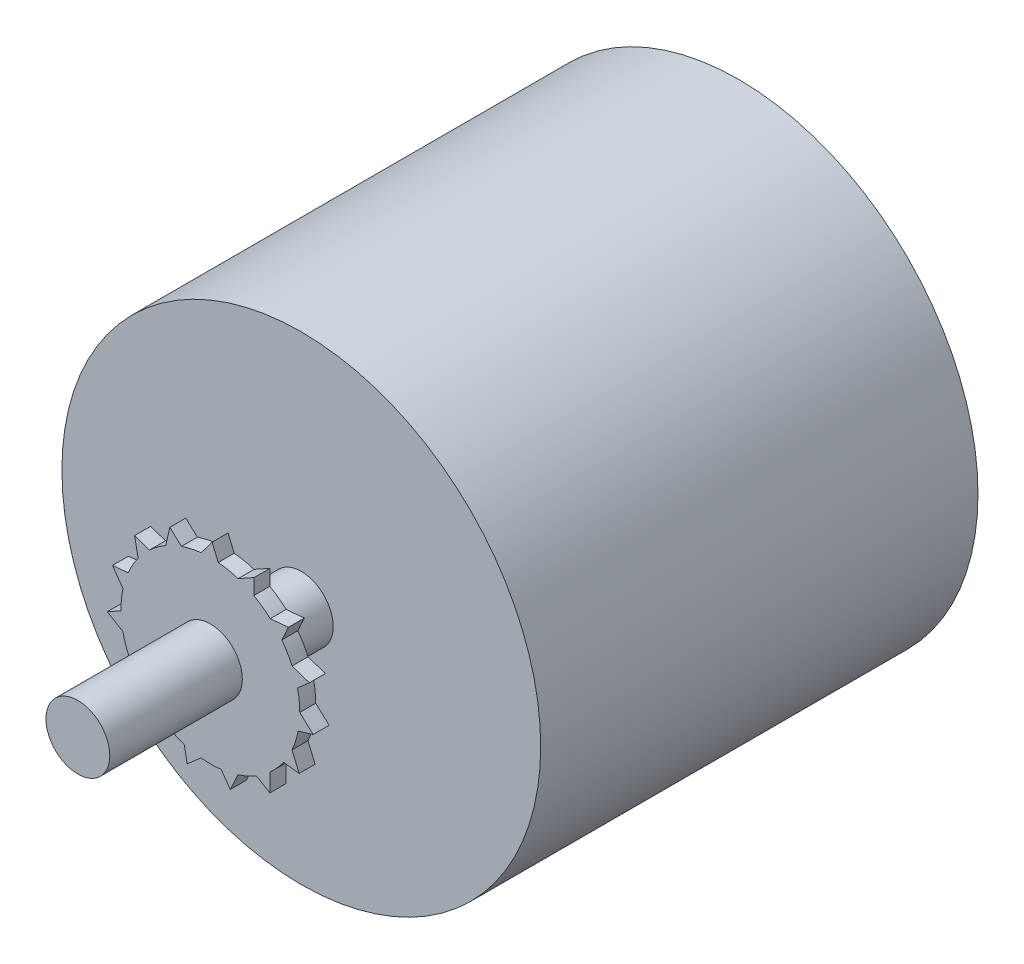
SolidWorks part; units mm, degrees
ref_plane "Front Plane" through (0, 0, 0) normal (0, 0, 1) x (1, 0, 0)
ref_plane "Top Plane" through (0, 0, 0) normal (0, 1, 0) x (1, 0, 0)
ref_plane "Right Plane" through (0, 0, 0) normal (1, 0, 0) x (0, 0, -1)
sketch "Sketch1" plane through (0, 0, 0) normal (0, 0, 1) x (1, 0, 0)
  circle A0 centre (0, 0) radius 75
  dimension "D1" = 150
extrude "Boss-Extrude1" add sketch "Sketch1" along normal blind 137
sketch "Sketch2" plane through (0, 0, 137) normal (0, 0, 1) x (1, 0, 0)
  line L0 (20.6249, 0) -> (-20.6249, 0) construction
  circle A0 centre (0, 0) radius 10
  point P6 (0, 0)
  dimension "D1" = 20
extrude "Boss-Extrude2" add sketch "Sketch2" along normal blind 70
ref_plane "Plane1" through (0, 0, 160.48) normal (0, 0, 1) x (1, 0, 0)
sketch "Sketch4" plane through (0, 0, 160.48) normal (0, 0, 1) x (1, 0, 0)
  circle A0 centre (0, 0) radius 28
  circle A1 centre (0, 0) radius 31 construction
  dimension "D1" = 56
  dimension "D2" = 62
extrude "Boss-Extrude3" add sketch "Sketch4" along normal blind 5
sketch "Sketch5" plane through (0, 0, 165.48) normal (0, 0, 1) x (1, 0, 0)
  line L1 (3.567, 25.3295) -> (0.5292, 32.4244)
  line L2 (0.5292, 32.4244) -> (-4.0963, 26.2461)
  line L3 (-4.0963, 26.2461) -> (3.567, 25.3295)
  circle A0 centre (0, 28) radius 2.228 construction
  circle A1 centre (0, 0) radius 28 construction
extrude "Boss-Extrude4" add sketch "Sketch5" against normal blind 5
pattern_circular "CirPattern1" count 15 over 360 about axis through (0, 0, 0) along (0, 0, 1) of "Boss-Extrude4"
